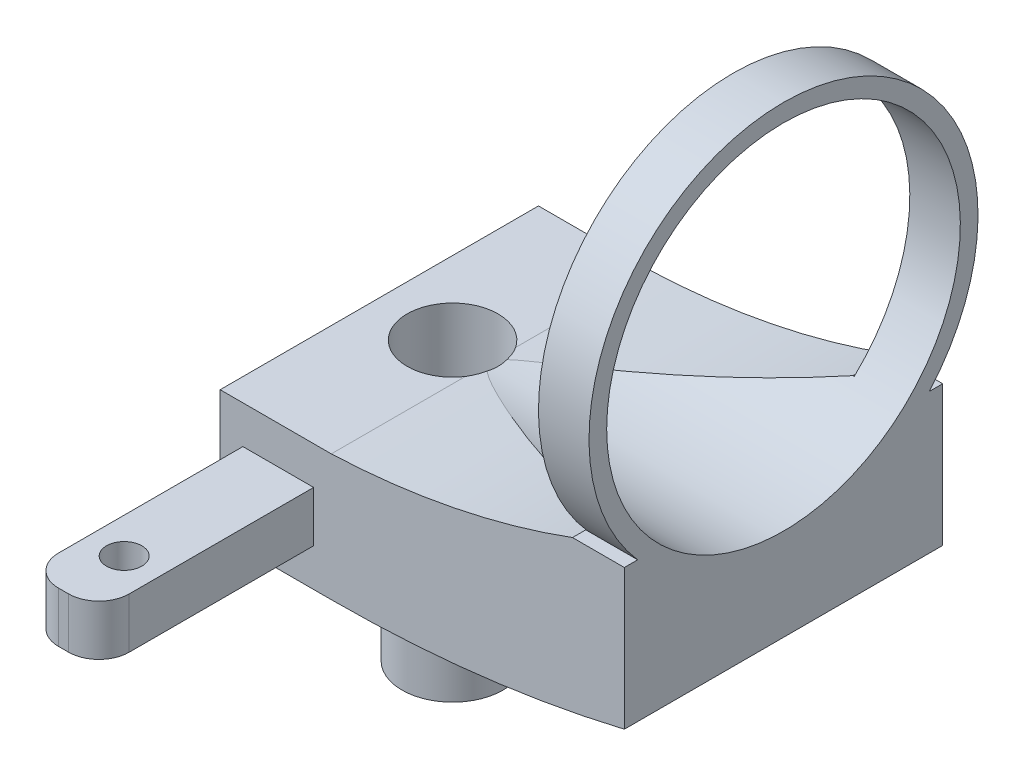
SolidWorks part; units mm, degrees
material "Cast Alloy Steel"
ref_plane "Front Plane" through (0, 0, 0) normal (0, 0, 1) x (1, 0, 0)
ref_plane "Top Plane" through (0, 0, 0) normal (0, 1, 0) x (1, 0, 0)
ref_plane "Right Plane" through (0, 0, 0) normal (1, 0, 0) x (0, 0, -1)
sketch "Sketch1" plane through (0, 0, 0) normal (0, 0, 1) x (1, 0, 0)
  line L0 (0, 0) -> (0, 25.0004)
  line L1 (0, 25.0004) -> (22, 25.0004)
  line L3 (22, 0) -> (0, 0)
  line L4 (0, 25.0004) -> (0, -234) construction
  line L8 (80, 38.7514) -> (80, 6.7987)
  arc A0 (22, 25.0004) -> (80, 38.7514) centre (15.9028, 179.9111) ccw
  arc A1 (22, 0) -> (80, 6.7987) centre (22, 250.8008) ccw
  dimension "D1" = 22
  dimension "D2" = 80
  dimension "D3" = 22
extrude "Boss-Extrude1" add sketch "Sketch1" along normal blind 48
sketch "Sketch2" plane through (0, 0, 48) normal (0, 0, 1) x (1, 0, 0)
  line L0 (0, 0) -> (0, 7.5) construction
  line L1 (0, 25.0004) -> (0, 0) construction
  line L2 (0, 7.5) -> (4.5, 7.5) construction
  line L3 (4.5, 7.5) -> (4.5, 17.5)
  line L4 (4.5, 17.5) -> (18.5, 17.5)
  line L5 (18.5, 17.5) -> (18.5, 7.5)
  line L6 (4.5, 7.5) -> (18.5, 7.5)
  dimension "D1" = 14
  dimension "D2" = 10
  dimension "D3" = 4.5
extrude "Boss-Extrude2" add sketch "Sketch2" along normal blind 50
ref_plane "Plane1" through (0, 0, 24) normal (0, 0, 1) x (1, 0, 0)
mirror "Mirror1" about plane through (0, 0, 24) normal (0, 0, 1) of "Boss-Extrude2"
sketch "Sketch3" plane through (0, 0, 0) normal (0, 1, 0) x (1, 0, 0)
  line L0 (11.5, 0) -> (11.5, 13.5)
  line L1 (18.5, 0) -> (4.5, 0) construction
  line L2 (11.5, 13.5) -> (-23.123, 13.5)
  line L3 (-23.123, 13.5) -> (-23.123, 84.8672)
  line L4 (-23.123, 84.8672) -> (32.759, 84.8672)
  line L5 (32.759, 84.8672) -> (32.759, 13.5)
  line L6 (32.759, 13.5) -> (11.5, 13.5)
extrude "Cut-Extrude1" cut sketch "Sketch3" along normal blind 98 contours L6 L5 L4 L3 L2
sketch "Sketch4" plane through (0, 17.5, 0) normal (0, 1, 0) x (1, 0, 0)
  line L0 (11.5, -48) -> (11.5, -86)
  line L1 (18.5, -48) -> (4.5, -48) construction
hole_wizard "M8x1.0 Tapped Hole1" positions "3DSketch1" profile "Sketch5" tap size "M8x1.0" standard "ANSI Metric"
sketch3d "3DSketch1"
  point P0 (11.5, 17.5, 86)
sketch "Sketch5" plane through (11.5, 17.5, 86) normal (1, 0, 0) x (0, 0, 1)
  line L0 (0, 0) -> (0, 12.103)
  line L1 (0, 12.103) -> (3.5, 10)
  line L2 (3.5, 10) -> (3.5, 0)
  line L5 (3.5, 0) -> (0, 0)
  line L10 (0, 12.103) -> (-3.5, 10) construction
  line L11 (0, -6.35) -> (0, 107.95) construction
  dimension "Tap Drill Dia." = 7
  dimension "Tap Drill Depth" = 10
  dimension "Drill Angle" = 118
cosmetic thread "Hole Thread1" parameters "D1"=10, "D2"=8
fillet "Fillet1" radius 6 2 edges at (4.5, 12.5, 98) (18.5, 12.5, 98)
ref_plane "Plane2" through (80, 0, 0) normal (-1, 0, 0) x (0, 0, 1)
sketch "Sketch7" plane through (80, 0, 0) normal (-1, 0, 0) x (0, 0, 1)
  line L0 (24, 25.0004) -> (24, 60.0004) construction
  line L1 (48, 25.0004) -> (0, 25.0004) construction
  circle A0 centre (24, 60.0004) radius 35
  circle A1 centre (24, 60.0004) radius 38.5
extrude "Boss-Extrude3" add sketch "Sketch7" along normal blind 10
sketch "Sketch8" plane through (80, 0, 0) normal (-1, 0, 0) x (0, 0, 1)
  circle A0 centre (24, 60.0004) radius 35
extrude "Cut-Extrude2" cut sketch "Sketch8" along normal blind 90
sketch "Sketch10" plane through (0, 0, 0) normal (0, -1, 0) x (1, 0, 0)
  line L0 (0, 24) -> (14.5, 24) construction
  line L1 (0, 48) -> (0, 0) construction
  circle A0 centre (14.5, 24) radius 12
  circle A1 centre (14.5, 24) radius 9
extrude "Boss-Extrude4" add sketch "Sketch10" along normal blind 5 and the other way blind 10
sketch "Sketch11" plane through (0, -5, 0) normal (0, -1, 0) x (1, 0, 0)
  circle A0 centre (14.5, 24) radius 10
  circle A1 centre (14.5, 24) radius 9
extrude "Boss-Extrude5" add sketch "Sketch11" along normal blind 25
sketch "Sketch12" plane through (0, 0, 0) normal (0, -1, 0) x (-1, 0, 0)
  circle A0 centre (-14.5, -24) radius 9
extrude "Cut-Extrude3" cut sketch "Sketch12" against normal blind 42
sketch "Sketch13" plane through (0, 0, 48) normal (0, 0, 1) x (1, 0, 0)
  line L0 (0, 25.0004) -> (0, 0)
  line L1 (0, 0) -> (22, 0)
  line L2 (0, 25.0004) -> (22, 25.0004)
  line L3 (69.7299, 34.5249) -> (70, 34.5249)
  line L6 (80, 29.8964) -> (80, 6.7987)
  line L10 (70, 34.5249) -> (80, 34.5249)
  line L11 (80, 29.8964) -> (80, 98.5004) construction
  line L12 (80, 34.5249) -> (80, 29.8964)
  arc A0 (22, 0) -> (80, 6.7987) centre (22, 250.8008) ccw construction
  arc A1 (22, 25.0004) -> (69.7299, 34.5249) centre (15.9028, 179.9111) ccw
  arc A2 (22, 0) -> (80, 6.7987) centre (22, 250.8008) ccw
extrude "Boss-Extrude6" add sketch "Sketch13" along normal blind 7.5
sketch "Sketch14" plane through (0, 0, 0) normal (0, 0, -1) x (-1, 0, 0)
  line L0 (-80, 29.8964) -> (-80, 6.7987)
  line L1 (-22, 0) -> (0, 0)
  line L2 (0, 0) -> (0, 25.0004)
  line L3 (0, 25.0004) -> (-22, 25.0004)
  line L4 (-69.7299, 34.5249) -> (-70, 34.5249)
  line L7 (-70, 34.5249) -> (-80, 34.5249)
  line L8 (-80, 98.5004) -> (-80, 29.8964) construction
  line L9 (-80, 34.5249) -> (-80, 29.8964)
  arc A0 (-80, 6.7987) -> (-22, 0) centre (-22, 250.8008) ccw
  arc A1 (-22, 25.0004) -> (-69.7299, 34.5249) centre (-15.9028, 179.9111) cw
extrude "Boss-Extrude7" add sketch "Sketch14" along normal blind 7.5
